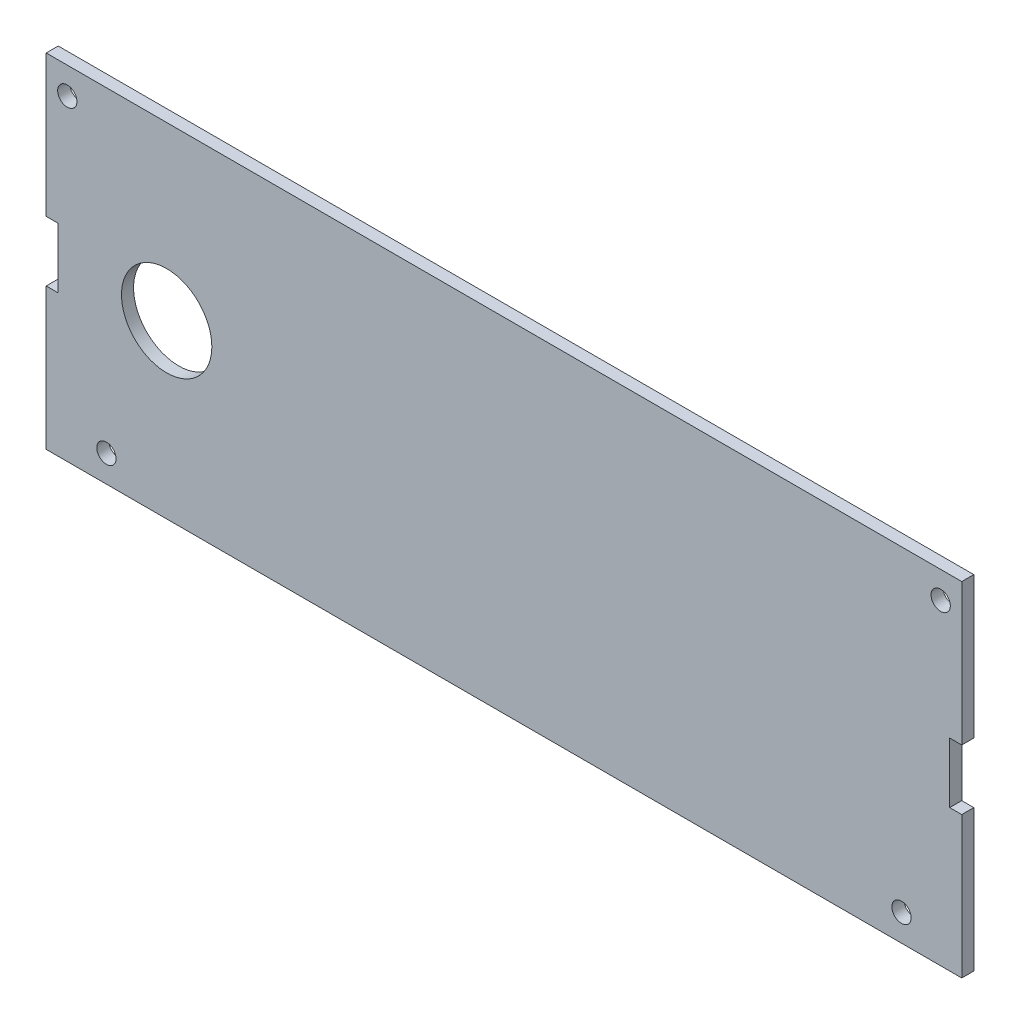
SolidWorks part; units mm, degrees
ref_plane "Front Plane" through (0, 0, 0) normal (0, 0, 1) x (1, 0, 0)
ref_plane "Top Plane" through (0, 0, 0) normal (0, 1, 0) x (1, 0, 0)
ref_plane "Right Plane" through (0, 0, 0) normal (1, 0, 0) x (0, 0, -1)
sketch "Sketch1" plane through (0, 0, 0) normal (0, 0, 1) x (1, 0, 0)
  line L0 (0, 11.7491) -> (0, -12.7107) construction
  line L1 (-76, 28.5) -> (76, 28.5)
  line L2 (-76, 28.5) -> (-76, -28.5)
  line L3 (-76, -28.5) -> (76, -28.5)
  line L4 (76, 28.5) -> (76, -28.5)
  line L5 (-76, 28.5) -> (76, -28.5) construction
  line L6 (-76, -28.5) -> (76, 28.5) construction
  line L7 (-74, 5) -> (-78, 5)
  line L8 (-74, 5) -> (-74, -5)
  line L9 (-74, -5) -> (-78, -5)
  line L10 (-78, 5) -> (-78, -5)
  line L11 (-74, 5) -> (-78, -5) construction
  line L12 (-74, -5) -> (-78, 5) construction
  line L13 (74, -5) -> (78, 5) construction
  line L14 (74, 5) -> (78, -5) construction
  line L15 (78, 5) -> (78, -5)
  line L16 (74, -5) -> (78, -5)
  line L17 (74, 5) -> (74, -5)
  line L18 (74, 5) -> (78, 5)
  point P0 (0, 0)
  point P6 (-76, 0)
  point P17 (76, 0)
  dimension "D1" = 57
  dimension "D2" = 152
  dimension "D3" = 10
  dimension "D4" = 4
extrude "Boss-Extrude1" add sketch "Sketch1" along normal blind 2 contours L17 L18 L4 L1 L2 L7 L8 L9 L3 L16
sketch "Sketch2" plane through (0, 0, 2) normal (0, 0, 1) x (1, 0, 0)
  line L1 (-76, -5) -> (-76, -28.5) construction
  circle A0 centre (-72.5, 24.05) radius 1.6
  circle A1 centre (72.5, 24.05) radius 1.6
  circle A2 centre (66, -24.05) radius 1.6
  circle A3 centre (-66, -24.05) radius 1.6
  circle A4 centre (-56, 0) radius 7.5
  dimension "D1" = 3.2
  dimension "D2" = 3.2
  dimension "D3" = 3.2
  dimension "D4" = 3.2
  dimension "D5" = 15
  dimension "D9" = 66
  dimension "D12" = 24.05
  dimension "D14" = 24.05
  dimension "D6" = 0
  dimension "D7" = 72.5
  dimension "D8" = 72.5
  dimension "D10" = 66
  dimension "D11" = 24.05
  dimension "D13" = 24.05
  dimension "D15" = 20
extrude "Cut-Extrude1" cut sketch "Sketch2" against normal through all
